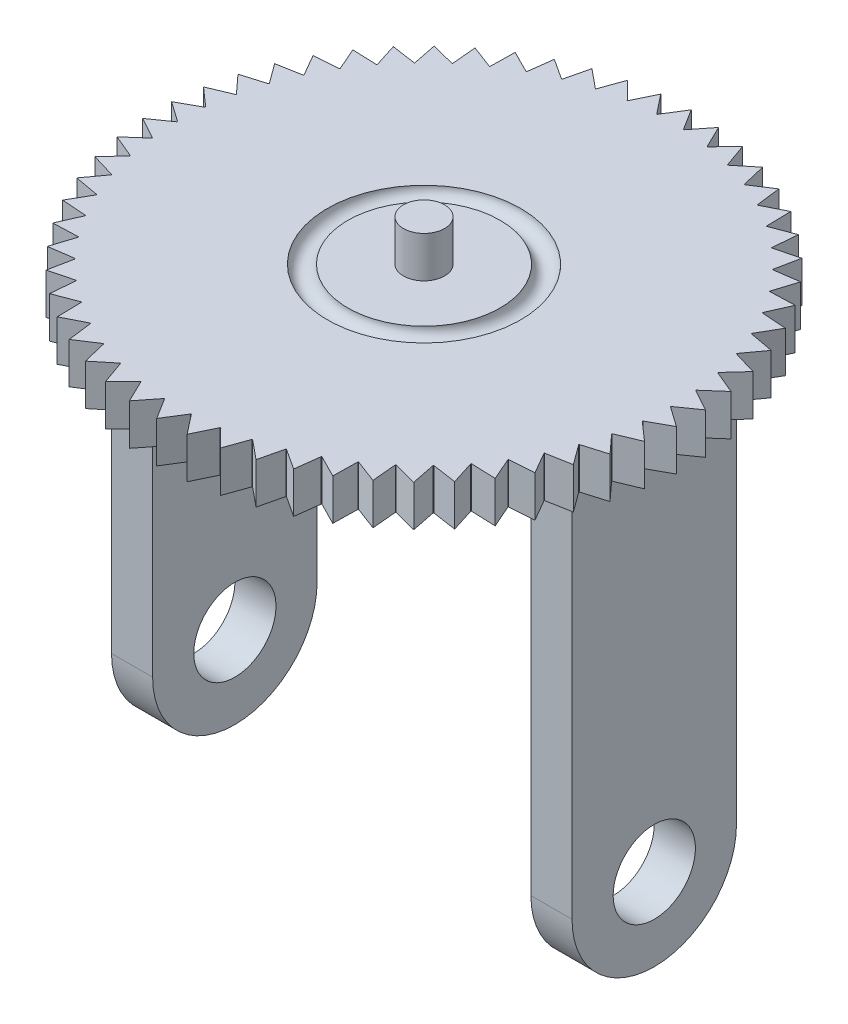
SolidWorks part; units mm, degrees
material "1023 Carbon Steel Sheet (SS)"
ref_plane "Front Plane" through (0, 0, 0) normal (0, 0, 1) x (1, 0, 0)
ref_plane "Top Plane" through (0, 0, 0) normal (0, 1, 0) x (1, 0, 0)
ref_plane "Right Plane" through (0, 0, 0) normal (1, 0, 0) x (0, 0, -1)
sketch "Sketch1" plane through (0, 0, 0) normal (0, 1, 0) x (1, 0, 0)
  circle A0 centre (0, 0) radius 76.2
  dimension "D1" = 152.4
extrude "Boss-Extrude1" add sketch "Sketch1" along normal blind 12.7 contours A0
sketch "Sketch2" plane through (0, 12.7, 0) normal (0, 1, 0) x (1, 0, 0)
  circle A0 centre (0, 0) radius 6.35
  dimension "D1" = 12.7
extrude "Boss-Extrude2" add sketch "Sketch2" along normal blind 12.7
sketch "Sketch4" plane through (0, 0, 0) normal (0, 0, 1) x (1, 0, 0)
  line L0 (76.2, 12.7) -> (-76.2, 12.7) construction
  line L1 (0, 0) -> (0, 24.8401)
  line L2 (-29.845, 12.7) -> (-23.495, 12.7)
  arc A0 (-29.845, 12.7) -> (-23.495, 12.7) centre (-26.67, 12.7) ccw
  dimension "D1" = 3.175
  dimension "D2" = 23.495
revolve "Cut-Revolve3" cut sketch "Sketch4" angle 360 about L1
sketch "Sketch5" plane through (0, 0, 0) normal (0, -1, 0) x (1, 0, 0)
  line L0 (0, -13.97) -> (0, 13.97) construction
  line L1 (58.42, -25.4) -> (71.12, -25.4)
  line L2 (58.42, -25.4) -> (58.42, 25.4)
  line L3 (58.42, 25.4) -> (71.12, 25.4)
  line L4 (71.12, -25.4) -> (71.12, 25.4)
  line L5 (58.42, -25.4) -> (71.12, 25.4) construction
  line L6 (58.42, 25.4) -> (71.12, -25.4) construction
  line L7 (-58.42, 25.4) -> (-71.12, 25.4)
  line L8 (-71.12, -25.4) -> (-71.12, 25.4)
  line L9 (-58.42, -25.4) -> (-71.12, -25.4)
  line L10 (-58.42, -25.4) -> (-58.42, 25.4)
  point P0 (64.77, 0)
  dimension "D1" = 50.8
  dimension "D2" = 12.7
  dimension "D3" = 64.77
extrude "Boss-Extrude3" add sketch "Sketch5" along normal blind 139.7
sketch "Sketch6" plane through (-71.12, 0, 0) normal (-1, 0, 0) x (0, 0, 1)
  line L0 (-25.4, -114.3) -> (-25.4, -139.7)
  line L1 (-25.4, -139.7) -> (-25.4, 0) construction
  line L2 (-25.4, -139.7) -> (25.4, -139.7)
  line L3 (25.4, -139.7) -> (25.4, -114.3)
  line L4 (25.4, -139.7) -> (25.4, 0) construction
  circle A0 centre (0, -114.3) radius 12.7
  arc A1 (-25.4, -114.3) -> (25.4, -114.3) centre (0, -114.3) ccw
  point P14 (0, -139.7)
  line M4 (-25.4, 0) -> (-25.4, -139.7)
  line M5 (-25.4, -139.7) -> (25.4, -139.7)
  line M6 (25.4, -139.7) -> (25.4, 0)
  dimension "D2" = 25.4
  dimension "D1" = 114.3
extrude "Cut-Extrude1" cut sketch "Sketch6" against normal through all contours A1 M4 M5 | A1 L2 M6 | A0
sketch "Sketch7" plane through (0, 12.7, 0) normal (0, 1, 0) x (1, 0, 0)
  line L0 (0, 76.2) -> (0, 82.55) construction
  line L1 (0, 82.55) -> (-4.0454, 76.0925)
  line L2 (0, 82.55) -> (4.0454, 76.0925)
  line L3 (-4.0454, 76.0925) -> (4.0454, 76.0925)
  line L4 (4.2053, 76.0839) -> (12.2488, 75.2091)
  line L5 (8.9252, 82.0661) -> (12.2488, 75.2091)
  line L6 (8.9252, 82.0661) -> (4.2053, 76.0839)
  line L7 (12.4068, 75.1832) -> (20.3085, 73.4439)
  line L8 (17.7458, 80.62) -> (20.3085, 73.4439)
  line L9 (17.7458, 80.62) -> (12.4068, 75.1832)
  line L10 (20.4628, 73.4011) -> (28.1301, 70.8176)
  line L11 (26.3583, 78.2288) -> (28.1301, 70.8176)
  line L12 (26.3583, 78.2288) -> (20.4628, 73.4011)
  line L13 (28.2789, 70.7584) -> (35.622, 67.3611)
  line L14 (34.6618, 74.9204) -> (35.622, 67.3611)
  line L15 (34.6618, 74.9204) -> (28.2789, 70.7584)
  line L16 (35.7634, 67.2861) -> (42.6962, 63.1148)
  line L17 (42.559, 70.7336) -> (42.6962, 63.1148)
  line L18 (42.559, 70.7336) -> (35.7634, 67.2861)
  line L19 (42.8287, 63.0249) -> (49.2698, 58.1285)
  line L20 (49.9571, 65.7175) -> (49.2698, 58.1285)
  line L21 (49.9571, 65.7175) -> (42.8287, 63.0249)
  line L22 (49.3918, 58.0249) -> (55.2658, 52.4608)
  line L23 (56.7696, 59.9309) -> (55.2658, 52.4608)
  line L24 (56.7696, 59.9309) -> (49.3918, 58.0249)
  line L25 (55.3759, 52.3445) -> (60.6138, 46.178)
  line L26 (62.9165, 53.4417) -> (60.6138, 46.178)
  line L27 (62.9165, 53.4417) -> (55.3759, 52.3445)
  line L28 (60.7107, 46.0505) -> (65.2512, 39.3538)
  line L29 (68.3257, 46.326) -> (65.2512, 39.3538)
  line L30 (68.3257, 46.326) -> (60.7107, 46.0505)
  line L31 (65.3338, 39.2166) -> (69.1236, 32.0682)
  line L32 (72.9339, 38.6671) -> (69.1236, 32.0682)
  line L33 (72.9339, 38.6671) -> (65.3338, 39.2166)
  line L34 (69.1908, 31.9229) -> (72.1856, 24.4066)
  line L35 (76.687, 30.5549) -> (72.1856, 24.4066)
  line L36 (76.687, 30.5549) -> (69.1908, 31.9229)
  line L37 (72.2367, 24.2549) -> (74.4012, 16.4589)
  line L38 (79.5411, 22.0845) -> (74.4012, 16.4589)
  line L39 (79.5411, 22.0845) -> (72.2367, 24.2549)
  line L40 (74.4357, 16.3026) -> (75.7446, 8.3183)
  line L41 (81.4625, 13.3551) -> (75.7446, 8.3183)
  line L42 (81.4625, 13.3551) -> (74.4357, 16.3026)
  line L43 (75.7619, 8.1591) -> (76.2, 0.0801)
  line L44 (82.4289, 4.4692) -> (76.2, 0.0801)
  line L45 (82.4289, 4.4692) -> (75.7619, 8.1591)
  line L46 (76.2, -0.0801) -> (75.7619, -8.1591)
  line L47 (82.4289, -4.4692) -> (75.7619, -8.1591)
  line L48 (82.4289, -4.4692) -> (76.2, -0.0801)
  line L49 (75.7446, -8.3183) -> (74.4357, -16.3026)
  line L50 (81.4625, -13.3551) -> (74.4357, -16.3026)
  line L51 (81.4625, -13.3551) -> (75.7446, -8.3183)
  line L52 (74.4012, -16.4589) -> (72.2367, -24.2549)
  line L53 (79.5411, -22.0845) -> (72.2367, -24.2549)
  line L54 (79.5411, -22.0845) -> (74.4012, -16.4589)
  line L55 (72.1856, -24.4066) -> (69.1908, -31.9229)
  line L56 (76.687, -30.5549) -> (69.1908, -31.9229)
  line L57 (76.687, -30.5549) -> (72.1856, -24.4066)
  line L58 (69.1236, -32.0682) -> (65.3338, -39.2166)
  line L59 (72.9339, -38.6671) -> (65.3338, -39.2166)
  line L60 (72.9339, -38.6671) -> (69.1236, -32.0682)
  line L61 (65.2512, -39.3538) -> (60.7107, -46.0505)
  line L62 (68.3257, -46.326) -> (60.7107, -46.0505)
  line L63 (68.3257, -46.326) -> (65.2512, -39.3538)
  line L64 (60.6138, -46.178) -> (55.3759, -52.3445)
  line L65 (62.9165, -53.4417) -> (55.3759, -52.3445)
  line L66 (62.9165, -53.4417) -> (60.6138, -46.178)
  line L67 (55.2658, -52.4608) -> (49.3918, -58.0249)
  line L68 (56.7696, -59.9309) -> (49.3918, -58.0249)
  line L69 (56.7696, -59.9309) -> (55.2658, -52.4608)
  line L70 (49.2698, -58.1285) -> (42.8287, -63.0249)
  line L71 (49.9571, -65.7175) -> (42.8287, -63.0249)
  line L72 (49.9571, -65.7175) -> (49.2698, -58.1285)
  line L73 (42.6962, -63.1148) -> (35.7634, -67.2861)
  line L74 (42.559, -70.7336) -> (35.7634, -67.2861)
  line L75 (42.559, -70.7336) -> (42.6962, -63.1148)
  line L76 (35.622, -67.3611) -> (28.2789, -70.7584)
  line L77 (34.6618, -74.9204) -> (28.2789, -70.7584)
  line L78 (34.6618, -74.9204) -> (35.622, -67.3611)
  line L79 (28.1301, -70.8176) -> (20.4628, -73.4011)
  line L80 (26.3583, -78.2288) -> (20.4628, -73.4011)
  line L81 (26.3583, -78.2288) -> (28.1301, -70.8176)
  line L82 (20.3085, -73.4439) -> (12.4068, -75.1832)
  line L83 (17.7458, -80.62) -> (12.4068, -75.1832)
  line L84 (17.7458, -80.62) -> (20.3085, -73.4439)
  line L85 (12.2488, -75.2091) -> (4.2053, -76.0839)
  line L86 (8.9252, -82.0661) -> (4.2053, -76.0839)
  line L87 (8.9252, -82.0661) -> (12.2488, -75.2091)
  line L88 (4.0454, -76.0925) -> (-4.0454, -76.0925)
  line L89 (0, -82.55) -> (-4.0454, -76.0925)
  line L90 (0, -82.55) -> (4.0454, -76.0925)
  line L91 (-4.2053, -76.0839) -> (-12.2488, -75.2091)
  line L92 (-8.9252, -82.0661) -> (-12.2488, -75.2091)
  line L93 (-8.9252, -82.0661) -> (-4.2053, -76.0839)
  line L94 (-12.4068, -75.1832) -> (-20.3085, -73.4439)
  line L95 (-17.7458, -80.62) -> (-20.3085, -73.4439)
  line L96 (-17.7458, -80.62) -> (-12.4068, -75.1832)
  line L97 (-20.4628, -73.4011) -> (-28.1301, -70.8176)
  line L98 (-26.3583, -78.2288) -> (-28.1301, -70.8176)
  line L99 (-26.3583, -78.2288) -> (-20.4628, -73.4011)
  line L100 (-28.2789, -70.7584) -> (-35.622, -67.3611)
  line L101 (-34.6618, -74.9204) -> (-35.622, -67.3611)
  line L102 (-34.6618, -74.9204) -> (-28.2789, -70.7584)
  line L103 (-35.7634, -67.2861) -> (-42.6962, -63.1148)
  line L104 (-42.559, -70.7336) -> (-42.6962, -63.1148)
  line L105 (-42.559, -70.7336) -> (-35.7634, -67.2861)
  line L106 (-42.8287, -63.0249) -> (-49.2698, -58.1285)
  line L107 (-49.9571, -65.7175) -> (-49.2698, -58.1285)
  line L108 (-49.9571, -65.7175) -> (-42.8287, -63.0249)
  line L109 (-49.3918, -58.0249) -> (-55.2658, -52.4608)
  line L110 (-56.7696, -59.9309) -> (-55.2658, -52.4608)
  line L111 (-56.7696, -59.9309) -> (-49.3918, -58.0249)
  line L112 (-55.3759, -52.3445) -> (-60.6138, -46.178)
  line L113 (-62.9165, -53.4417) -> (-60.6138, -46.178)
  line L114 (-62.9165, -53.4417) -> (-55.3759, -52.3445)
  line L115 (-60.7107, -46.0505) -> (-65.2512, -39.3538)
  line L116 (-68.3257, -46.326) -> (-65.2512, -39.3538)
  line L117 (-68.3257, -46.326) -> (-60.7107, -46.0505)
  line L118 (-65.3338, -39.2166) -> (-69.1236, -32.0682)
  line L119 (-72.9339, -38.6671) -> (-69.1236, -32.0682)
  line L120 (-72.9339, -38.6671) -> (-65.3338, -39.2166)
  line L121 (-69.1908, -31.9229) -> (-72.1856, -24.4066)
  line L122 (-76.687, -30.5549) -> (-72.1856, -24.4066)
  line L123 (-76.687, -30.5549) -> (-69.1908, -31.9229)
  line L124 (-72.2367, -24.2549) -> (-74.4012, -16.4589)
  line L125 (-79.5411, -22.0845) -> (-74.4012, -16.4589)
  line L126 (-79.5411, -22.0845) -> (-72.2367, -24.2549)
  line L127 (-74.4357, -16.3026) -> (-75.7446, -8.3183)
  line L128 (-81.4625, -13.3551) -> (-75.7446, -8.3183)
  line L129 (-81.4625, -13.3551) -> (-74.4357, -16.3026)
  line L130 (-75.7619, -8.1591) -> (-76.2, -0.0801)
  line L131 (-82.4289, -4.4692) -> (-76.2, -0.0801)
  line L132 (-82.4289, -4.4692) -> (-75.7619, -8.1591)
  line L133 (-76.2, 0.0801) -> (-75.7619, 8.1591)
  line L134 (-82.4289, 4.4692) -> (-75.7619, 8.1591)
  line L135 (-82.4289, 4.4692) -> (-76.2, 0.0801)
  line L136 (-75.7446, 8.3183) -> (-74.4357, 16.3026)
  line L137 (-81.4625, 13.3551) -> (-74.4357, 16.3026)
  line L138 (-81.4625, 13.3551) -> (-75.7446, 8.3183)
  line L139 (-74.4012, 16.4589) -> (-72.2367, 24.2549)
  line L140 (-79.5411, 22.0845) -> (-72.2367, 24.2549)
  line L141 (-79.5411, 22.0845) -> (-74.4012, 16.4589)
  line L142 (-72.1856, 24.4066) -> (-69.1908, 31.9229)
  line L143 (-76.687, 30.5549) -> (-69.1908, 31.9229)
  line L144 (-76.687, 30.5549) -> (-72.1856, 24.4066)
  line L145 (-69.1236, 32.0682) -> (-65.3338, 39.2166)
  line L146 (-72.9339, 38.6671) -> (-65.3338, 39.2166)
  line L147 (-72.9339, 38.6671) -> (-69.1236, 32.0682)
  line L148 (-65.2512, 39.3538) -> (-60.7107, 46.0505)
  line L149 (-68.3257, 46.326) -> (-60.7107, 46.0505)
  line L150 (-68.3257, 46.326) -> (-65.2512, 39.3538)
  line L151 (-60.6138, 46.178) -> (-55.3759, 52.3445)
  line L152 (-62.9165, 53.4417) -> (-55.3759, 52.3445)
  line L153 (-62.9165, 53.4417) -> (-60.6138, 46.178)
  line L154 (-55.2658, 52.4608) -> (-49.3918, 58.0249)
  line L155 (-56.7696, 59.9309) -> (-49.3918, 58.0249)
  line L156 (-56.7696, 59.9309) -> (-55.2658, 52.4608)
  line L157 (-49.2698, 58.1285) -> (-42.8287, 63.0249)
  line L158 (-49.9571, 65.7175) -> (-42.8287, 63.0249)
  line L159 (-49.9571, 65.7175) -> (-49.2698, 58.1285)
  line L160 (-42.6962, 63.1148) -> (-35.7634, 67.2861)
  line L161 (-42.559, 70.7336) -> (-35.7634, 67.2861)
  line L162 (-42.559, 70.7336) -> (-42.6962, 63.1148)
  line L163 (-35.622, 67.3611) -> (-28.2789, 70.7584)
  line L164 (-34.6618, 74.9204) -> (-28.2789, 70.7584)
  line L165 (-34.6618, 74.9204) -> (-35.622, 67.3611)
  line L166 (-28.1301, 70.8176) -> (-20.4628, 73.4011)
  line L167 (-26.3583, 78.2288) -> (-20.4628, 73.4011)
  line L168 (-26.3583, 78.2288) -> (-28.1301, 70.8176)
  line L169 (-20.3085, 73.4439) -> (-12.4068, 75.1832)
  line L170 (-17.7458, 80.62) -> (-12.4068, 75.1832)
  line L171 (-17.7458, 80.62) -> (-20.3085, 73.4439)
  line L172 (-12.2488, 75.2091) -> (-4.2053, 76.0839)
  line L173 (-8.9252, 82.0661) -> (-4.2053, 76.0839)
  line L174 (-8.9252, 82.0661) -> (-12.2488, 75.2091)
  circle A0 centre (0, 0) radius 76.2 construction
  point P182 (0, 0)
  dimension "D1" = 6.35
  dimension "D2" = 7.62
  dimension "D3" = 58
extrude "Boss-Extrude4" add sketch "Sketch7" against normal blind 12.7
